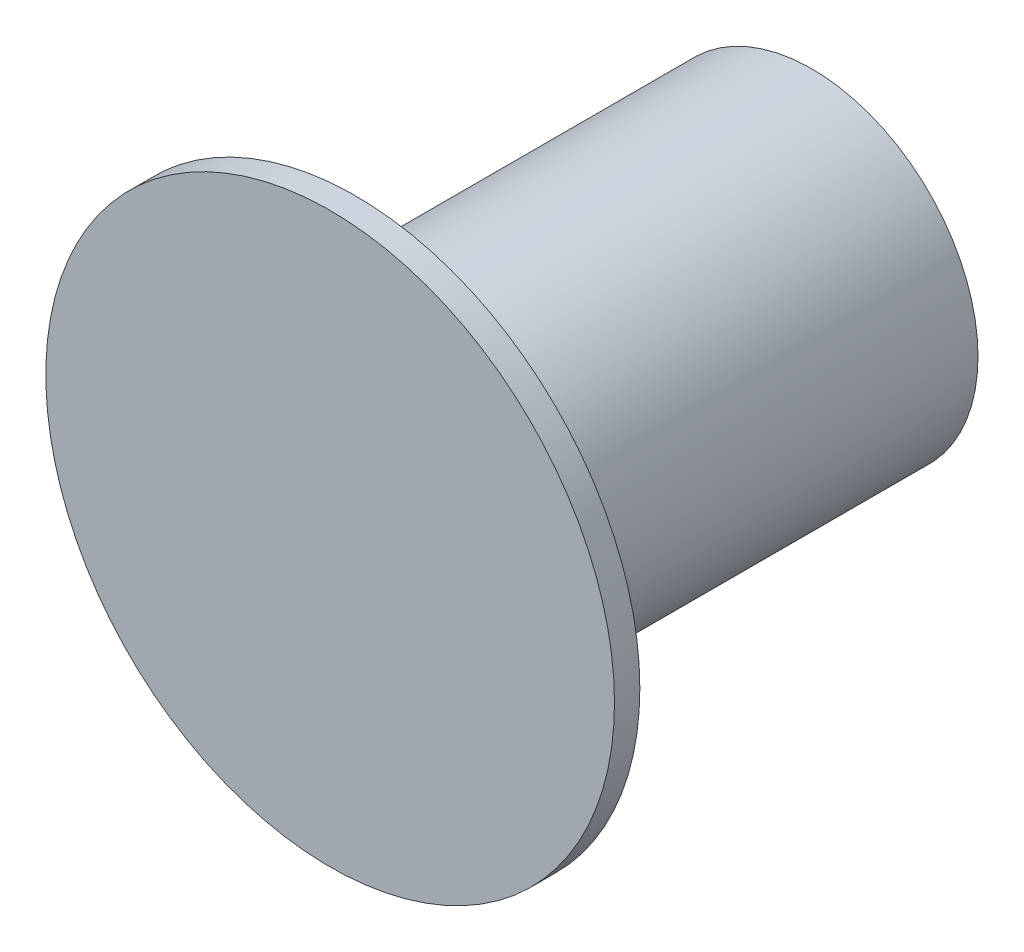
SolidWorks part; units mm, degrees
ref_plane "Front Plane" through (0, 0, 0) normal (0, 0, 1) x (1, 0, 0)
ref_plane "Top Plane" through (0, 0, 0) normal (0, 1, 0) x (1, 0, 0)
ref_plane "Right Plane" through (0, 0, 0) normal (1, 0, 0) x (0, 0, -1)
sketch "Sketch2" plane through (0, 0, -10) normal (0, 0, 1) x (1, 0, 0)
  circle A0 centre (-12.3823, -201.4807) radius 6.5497 construction
  circle A1 centre (-12.3823, -201.4807) radius 6.5497
extrude "Boss-Extrude1" add sketch "Sketch2" against normal blind 18
sketch "Sketch3" plane through (0, 0, -10) normal (0, 0, 1) x (1, 0, 0)
  circle A0 centre (-12.3823, -201.4807) radius 11.2138
extrude "Boss-Extrude2" add sketch "Sketch3" along normal blind 1
